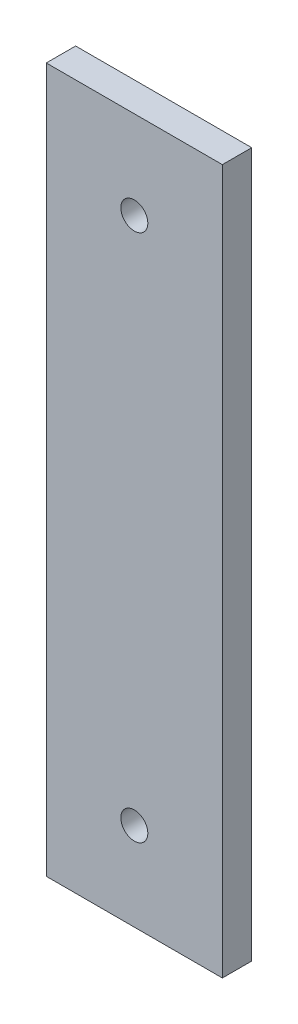
SolidWorks part; units mm, degrees
ref_plane "Front Plane" through (0, 0, 0) normal (0, 0, 1) x (1, 0, 0)
ref_plane "Top Plane" through (0, 0, 0) normal (0, 1, 0) x (1, 0, 0)
ref_plane "Right Plane" through (0, 0, 0) normal (1, 0, 0) x (0, 0, -1)
sketch "Sketch2" plane through (0, 0, 0) normal (0, 0, 1) x (1, 0, 0)
  line L1 (0, 0) -> (19.05, 0)
  line L2 (0, 0) -> (0, 76.2)
  line L3 (0, 76.2) -> (19.05, 76.2)
  line L4 (19.05, 0) -> (19.05, 76.2)
  dimension "D1" = 19.05
  dimension "D2" = 76.2
extrude "Boss-Extrude1" add sketch "Sketch2" along normal blind 3.175
sketch "Sketch3" plane through (0, 0, 3.175) normal (0, 0, 1) x (1, 0, 0)
  line L2 (19.05, 76.2) -> (0, 76.2) construction
  circle A0 centre (9.525, 66.675) radius 1.4605
  circle A1 centre (9.525, 9.525) radius 1.4605
  dimension "D1" = 57.15
  dimension "D2" = 2.921
  dimension "D3" = 2.921
  dimension "D4" = 9.525
extrude "Cut-Extrude1" cut sketch "Sketch3" against normal through all
